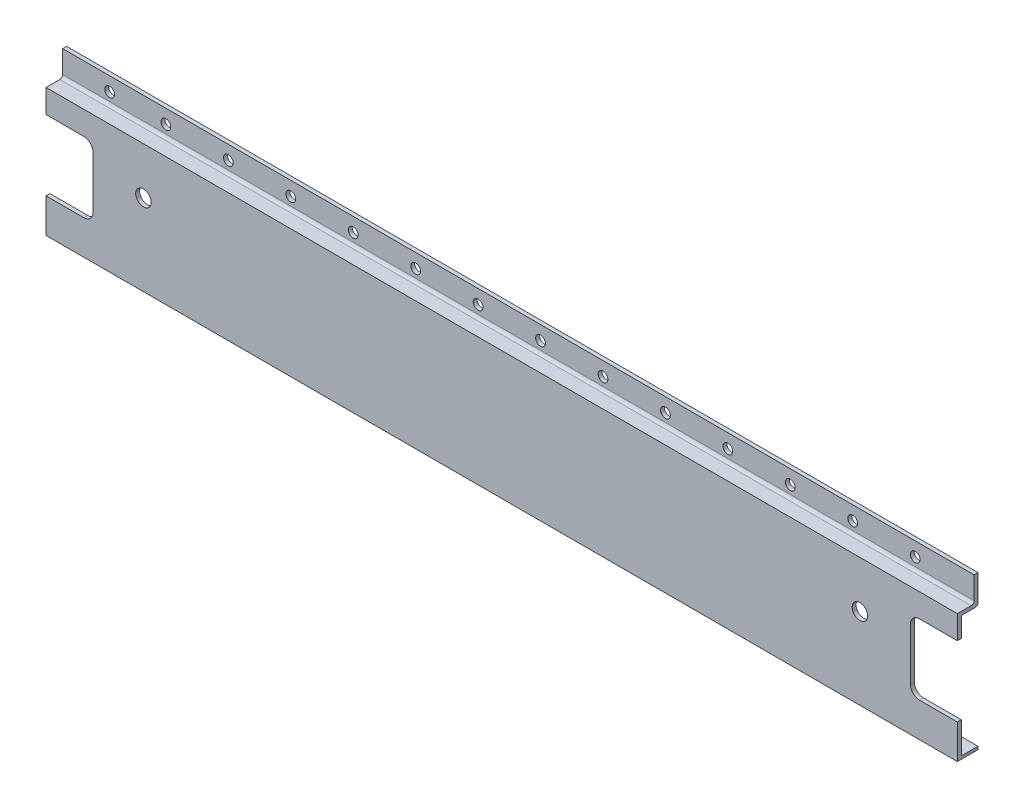
SolidWorks part; units mm, degrees
material "Alloy Steel (SS)"
ref_plane "Front Plane" through (0, 0, 0) normal (0, 0, 1) x (1, 0, 0)
ref_plane "Top Plane" through (0, 0, 0) normal (0, 1, 0) x (1, 0, 0)
ref_plane "Right Plane" through (0, 0, 0) normal (1, 0, 0) x (0, 0, -1)
sketch "Sketch1" plane through (0, 0, 0) normal (0, 0, 1) x (1, 0, 0)
  line L1 (-320.675, -53.975) -> (320.675, -53.975)
  line L2 (-320.675, -53.975) -> (-320.675, 53.975)
  line L3 (-320.675, 53.975) -> (320.675, 53.975)
  line L4 (320.675, -53.975) -> (320.675, 53.975)
  line L5 (-320.675, -53.975) -> (320.675, 53.975) construction
  line L6 (-320.675, 53.975) -> (320.675, -53.975) construction
  point P0 (0, 0)
  dimension "D1" = 107.95
  dimension "D2" = 641.35
extrude "Boss-Extrude1" add sketch "Sketch1" along normal blind 14.5161
sketch "Sketch2" plane through (0, 0, 14.5161) normal (0, 0, 1) x (1, 0, 0)
  line L0 (320.675, -53.975) -> (320.675, 53.975) construction
  line L1 (-320.675, 53.975) -> (320.675, 53.975)
  line L2 (-320.675, 53.975) -> (-320.675, 36.195)
  line L3 (-320.675, 36.195) -> (320.675, 36.195)
  line L4 (320.675, 53.975) -> (320.675, 36.195)
  dimension "D1" = 17.78
extrude "Cut-Extrude1" cut sketch "Sketch2" against normal blind 11.7602
sketch "Sketch3" plane through (0, 0, 0) normal (0, 0, -1) x (-1, 0, 0)
  line L0 (-320.675, 53.975) -> (-320.675, 33.655)
  line L1 (-320.675, -53.975) -> (-320.675, 53.975) construction
  line L2 (320.675, 53.975) -> (320.675, -53.975) construction
  line L3 (-320.675, 33.655) -> (320.675, 33.655)
  line L4 (-320.675, 33.655) -> (-320.675, -51.8795)
  line L5 (-320.675, -51.8795) -> (320.675, -51.8795)
  line L6 (320.675, 33.655) -> (320.675, -51.8795)
  line L7 (320.675, -53.975) -> (-320.675, -53.975) construction
  line M3 (-320.675, 53.975) -> (-320.675, -53.975)
  line M5 (320.675, -53.975) -> (320.675, 53.975)
  dimension "D1" = 20.32
  dimension "D2" = 2.0955
extrude "Cut-Extrude3" cut sketch "Sketch3" against normal blind 11.7602 contours L5 L3 M3 M5
fillet "Fillet1" radius 2.032 2 edges at (0, 36.195, 2.7559) (0, 33.655, 0)
sketch "Sketch4" plane through (0, 0, 11.7602) normal (0, 0, -1) x (-1, 0, 0)
  line L0 (0, -51.8795) -> (0, -13.5829)
  line L1 (-320.675, 33.655) -> (-320.675, -51.8795) construction
  line L2 (-320.675, 19.685) -> (-294.005, 19.685)
  line L3 (-287.655, 13.335) -> (-287.655, -23.495)
  line L4 (-294.005, -29.845) -> (-320.675, -29.845)
  line L5 (-320.675, -29.845) -> (-320.675, 19.685)
  line L6 (-320.675, -51.8795) -> (320.675, -51.8795) construction
  line L7 (320.675, -29.845) -> (320.675, 19.685)
  line L8 (294.005, -29.845) -> (320.675, -29.845)
  line L9 (287.655, 13.335) -> (287.655, -23.495)
  line L10 (320.675, 19.685) -> (294.005, 19.685)
  arc A0 (-294.005, -29.845) -> (-287.655, -23.495) centre (-294.005, -23.495) ccw
  arc A1 (-287.655, 13.335) -> (-294.005, 19.685) centre (-294.005, 13.335) ccw
  arc A2 (287.655, 13.335) -> (294.005, 19.685) centre (294.005, 13.335) cw
  arc A3 (294.005, -29.845) -> (287.655, -23.495) centre (294.005, -23.495) cw
  point P11 (-287.655, 19.685)
  point P25 (287.655, 19.685)
  line M9 (-320.675, 33.655) -> (-320.675, -51.8795)
  line M11 (320.675, -51.8795) -> (320.675, 33.655)
  dimension "D3" = 6.35
  dimension "D1" = 33.02
  dimension "D2" = 49.53
extrude "Cut-Extrude4" cut sketch "Sketch4" against normal through all contours L3 A1 L2 L4 A0 M9 | A3 L8 L10 A2 L9 M11
sketch "Sketch5" plane through (0, 0, 0) normal (0, 0, -1) x (-1, 0, 0)
  line L0 (320.675, 53.975) -> (320.675, 38.227) construction
  circle A0 centre (-279.2221, 44.1482) radius 3.429
  circle A1 centre (-235.2801, 44.1482) radius 3.429
  circle A2 centre (-191.3381, 44.1482) radius 3.429
  circle A3 centre (-147.3961, 44.1482) radius 3.429
  circle A4 centre (-103.4541, 44.1482) radius 3.429
  circle A5 centre (-59.5121, 44.1482) radius 3.429
  circle A6 centre (-15.5701, 44.1482) radius 3.429
  circle A7 centre (28.3719, 44.1482) radius 3.429
  circle A8 centre (72.3139, 44.1482) radius 3.429
  circle A9 centre (116.2559, 44.1482) radius 3.429
  circle A10 centre (160.1979, 44.1482) radius 3.429
  circle A11 centre (204.1399, 44.1482) radius 3.429
  circle A12 centre (248.0819, 44.1482) radius 3.429
  circle A13 centre (287.655, 44.1482) radius 3.429
  dimension "D1" = 6.858
  dimension "D2" = 33.02
extrude "Cut-Extrude5" cut sketch "Sketch5" against normal blind 11.7602 contours A0 | A1 | A2 | A3 | A4 | A6 | A5 | A7 | A8 | A9 | A10 | A13 | A12 | A11
sketch "Sketch6" plane through (0, 0, 11.7602) normal (0, 0, -1) x (-1, 0, 0)
  line L0 (-287.655, -5.08) -> (-252.095, -5.08)
  line L1 (-287.655, 13.335) -> (-287.655, -23.495) construction
  line L2 (-252.095, 53.975) -> (-252.095, 3.175)
  line L3 (-320.675, 53.975) -> (320.675, 53.975) construction
  line L4 (0, 0) -> (0, 74.9965)
  circle A0 centre (-252.095, 3.175) radius 5.461
  circle A1 centre (252.095, 3.175) radius 5.461
  dimension "D3" = 10.922
  dimension "D1" = 35.56
  dimension "D2" = 50.8
extrude "Cut-Extrude6" cut sketch "Sketch6" against normal blind 11.7602
sketch "Sketch7" plane through (0, -51.8795, 0) normal (0, 1, 0) x (1, 0, 0)
  line L0 (0, 0) -> (0, -11.7602)
  line L2 (320.675, 0) -> (-320.675, 0) construction
  line L3 (320.675, -11.7602) -> (-320.675, -11.7602) construction
  circle A0 centre (-206.375, -5.8801) radius 2.54
  circle A1 centre (-197.485, -5.8801) radius 2.54
  circle A2 centre (-188.595, -5.8801) radius 2.54
  circle A3 centre (188.595, -5.8801) radius 2.54
  circle A4 centre (197.485, -5.8801) radius 2.54
  circle A5 centre (206.375, -5.8801) radius 2.54
extrude "Cut-Extrude7" cut sketch "Sketch7" against normal blind 2.54 contours A0 | A1 | A2 | A4 | A3 | A5
sketch "Sketch8" plane through (0, -51.8795, 0) normal (0, 1, 0) x (1, 0, 0)
  line L1 (-320.675, 0) -> (320.675, 0)
  line L2 (-320.675, 0) -> (-320.675, 17.018)
  line L3 (-320.675, 17.018) -> (320.675, 17.018)
  line L4 (320.675, 0) -> (320.675, 17.018)
  dimension "D1" = 17.018
extrude "Boss-Extrude2" add sketch "Sketch8" along normal blind 16.764 and the other way up to surface (2.0955 mm away) separate body contours L2 L1 L4 L3 other way up to face at (-197.485, -53.975, 8.4201)
sketch "Sketch9" plane through (0, -35.1155, 0) normal (0, 1, 0) x (1, 0, 0)
  line L0 (320.675, 0) -> (-320.675, 0) construction
  line L1 (-320.675, 17.018) -> (-250.825, 17.018)
  line L2 (-320.675, 17.018) -> (-320.675, 0)
  line L3 (-320.675, 0) -> (-250.825, 0)
  line L4 (-250.825, 17.018) -> (-250.825, 0)
  line L5 (0, 0) -> (0, 55.9843)
  line L6 (250.825, 17.018) -> (250.825, 0)
  line L7 (320.675, 0) -> (250.825, 0)
  line L8 (320.675, 17.018) -> (320.675, 0)
  line L9 (320.675, 17.018) -> (250.825, 17.018)
  line M6 (320.675, 17.018) -> (-320.675, 17.018)
  line M7 (-320.675, 17.018) -> (-320.675, 0)
  line M8 (-320.675, 0) -> (320.675, 0)
  line M9 (320.675, 0) -> (320.675, 17.018)
  dimension "D1" = 69.85
extrude "Cut-Extrude8" cut sketch "Sketch9" against normal through all contours L6 M6 M8 M9 | L4 M6 M7 M8
shell "Shell1" thickness 2.032
sketch "Sketch10" plane through (0, 0, -17.018) normal (0, 0, -1) x (-1, 0, 0)
  line L0 (250.825, -53.975) -> (250.825, -35.1155) construction
  line L1 (-250.825, -53.975) -> (250.825, -53.975)
  line L2 (-250.825, -53.975) -> (-250.825, -38.735)
  line L3 (-250.825, -38.735) -> (250.825, -38.735)
  line L4 (250.825, -53.975) -> (250.825, -38.735)
  dimension "D1" = 15.24
extrude "Cut-Extrude9" cut sketch "Sketch10" against normal blind 14.986
fillet "Fillet2" radius 3.175 1 edges at (0, -35.1155, 0)
sketch "Sketch11" plane through (0, -35.1155, 0) normal (0, 1, 0) x (1, 0, 0)
  line L0 (0, 3.175) -> (0, 25.4881)
  line L2 (-250.825, 3.175) -> (250.825, 3.175) construction
  circle A0 centre (-244.475, 10.0965) radius 3.175
  circle A1 centre (244.475, 10.0965) radius 3.175
extrude "Cut-Extrude10" cut sketch "Sketch11" against normal blind 16.764 contours A0 | A1
